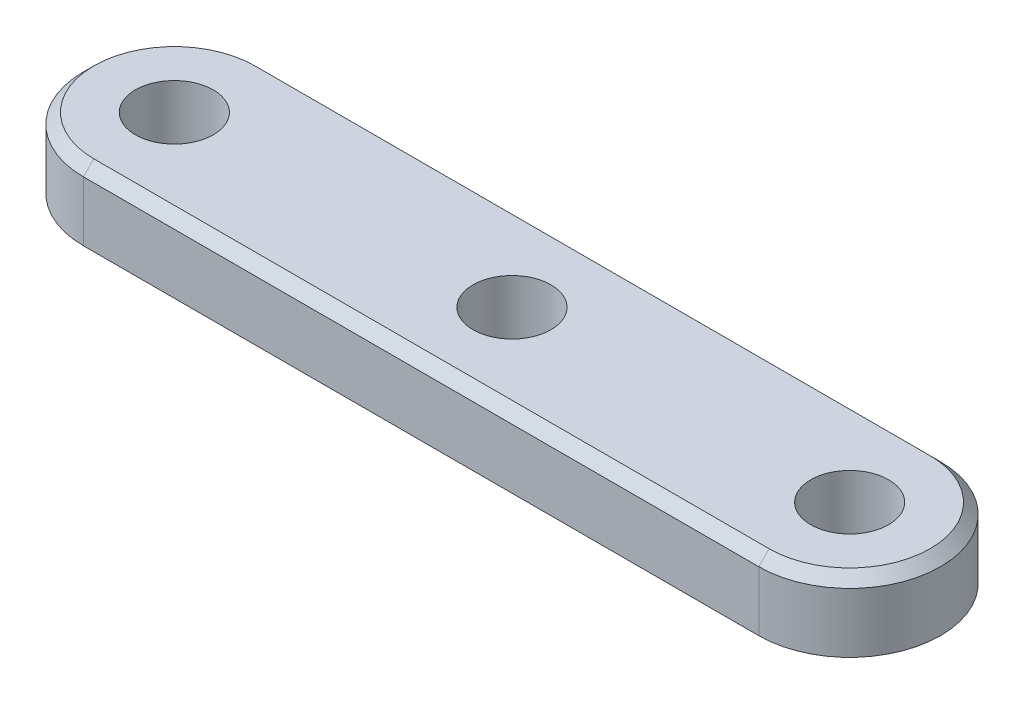
SolidWorks part; units mm, degrees
ref_plane "Front Plane" through (0, 0, 0) normal (0, 0, 1) x (1, 0, 0)
ref_plane "Top Plane" through (0, 0, 0) normal (0, 1, 0) x (1, 0, 0)
ref_plane "Right Plane" through (0, 0, 0) normal (1, 0, 0) x (0, 0, -1)
sketch "Sketch1" plane through (0, 0, 0) normal (0, 1, 0) x (1, 0, 0)
  line L0 (-18.0944, 0) -> (24.4801, 0) construction
  line L1 (-13, 0) -> (13, 0) construction
  line L2 (-13, 3.5) -> (13, 3.5)
  line L3 (-13, -3.5) -> (13, -3.5)
  line L4 (0, 10.1131) -> (0, -14.786) construction
  arc A0 (-13, 3.5) -> (-13, -3.5) centre (-13, 0) ccw
  arc A1 (13, -3.5) -> (13, 3.5) centre (13, 0) ccw
  circle A2 centre (-13, 0) radius 1.5
  circle A4 centre (13, 0) radius 1.5
  circle A5 centre (0, 0) radius 1.5
  point P5 (0, 0)
  point P11 (-16.5, 0)
  point P12 (16.5, 0)
  dimension "D3" = 3
  dimension "D4" = 3
  dimension "D1" = 7
  dimension "D2" = 33
extrude "Boss-Extrude1" add sketch "Sketch1" along normal mid plane 2.7
chamfer "Chamfer1" distance 0.4 angle 45 4 edges at (16.5, 1.35, 0) (0, 1.35, -3.5) (-16.5, 1.35, 0) (0, 1.35, 3.5)
